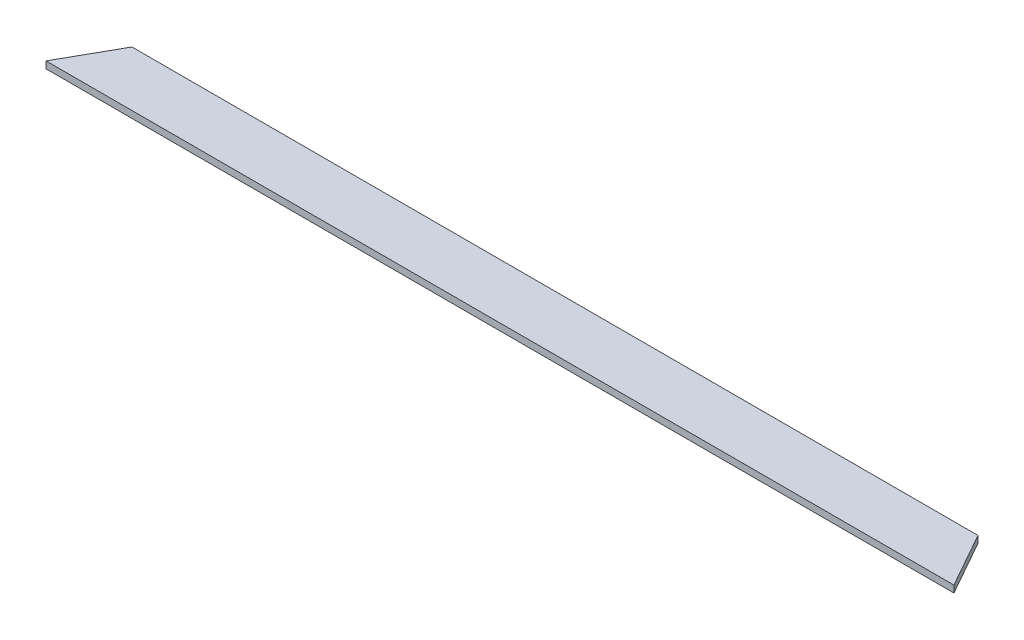
SolidWorks part; units mm, degrees
material "6061 Alloy"
ref_plane "Front Plane" through (0, 0, 0) normal (0, 0, 1) x (1, 0, 0)
ref_plane "Top Plane" through (0, 0, 0) normal (0, 1, 0) x (1, 0, 0)
ref_plane "Right Plane" through (0, 0, 0) normal (1, 0, 0) x (0, 0, -1)
sketch "Sketch1" plane through (0, 0, 0) normal (0, 1, 0) x (1, 0, 0)
  line L0 (0, 0) -> (195.2625, 0)
  line L1 (195.2625, 0) -> (209.55, -25.4)
  line L2 (209.55, -25.4) -> (-209.55, -25.4)
  line L3 (-209.55, -25.4) -> (-195.2625, 0)
  line L4 (-195.2625, 0) -> (0, 0)
  point P3 (0, -25.4)
  dimension "D1" = 419.1
  dimension "D2" = 25.4
  dimension "D3" = 195.2625
  dimension "D4" = 195.2625
extrude "Boss-Extrude1" add sketch "Sketch1" along normal blind 3.175
